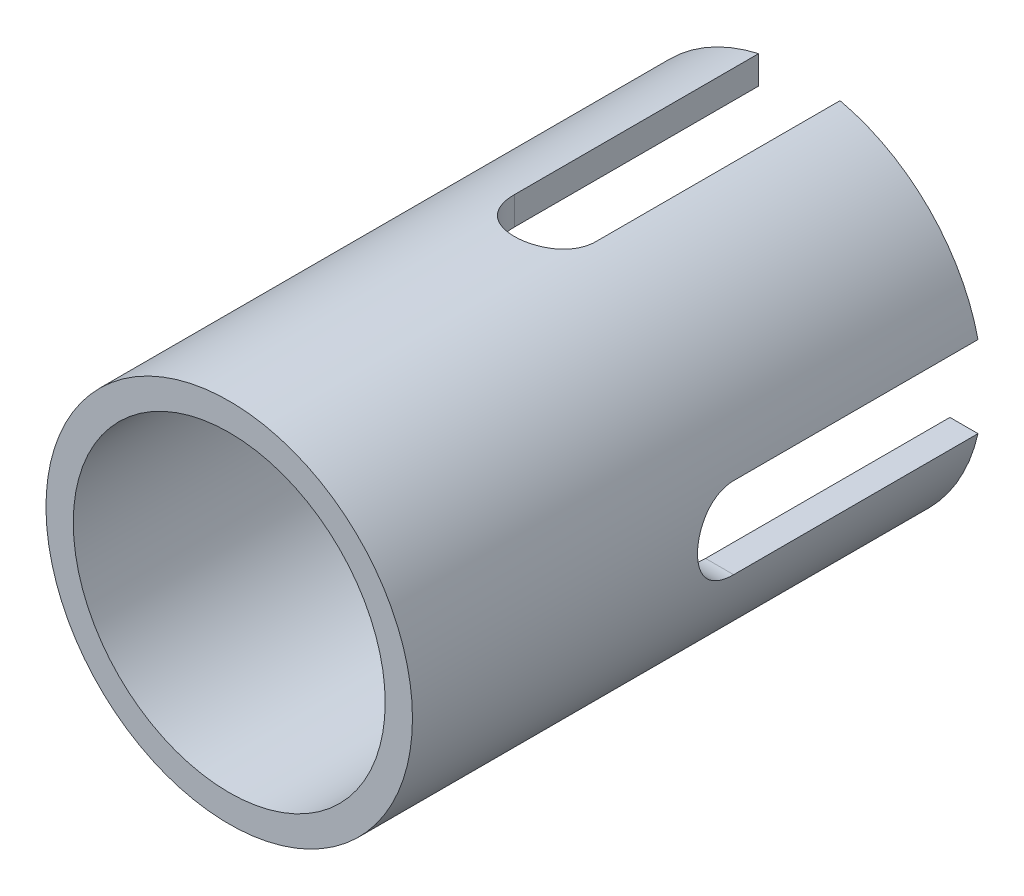
SolidWorks part; units mm, degrees
ref_plane "Front Plane" through (0, 0, 0) normal (0, 0, 1) x (1, 0, 0)
ref_plane "Top Plane" through (0, 0, 0) normal (0, 1, 0) x (1, 0, 0)
ref_plane "Right Plane" through (0, 0, 0) normal (1, 0, 0) x (0, 0, -1)
sketch "Sketch12" plane through (0, 0, 0) normal (0, 0, 1) x (1, 0, 0)
  circle A0 centre (0, 0) radius 48.641
  circle A1 centre (0, 0) radius 57.15
  dimension "D1" = 114.3
  dimension "D2" = 97.282
extrude "Boss-Extrude1" add sketch "Sketch12" along normal blind 177.8
sketch "Sketch13" plane through (0, 0, 0) normal (0, 1, 0) x (1, 0, 0)
  line L0 (-12.7, 0) -> (12.7, 0)
  line L1 (57.15, 0) -> (-57.15, 0) construction
  line L2 (12.7, 0) -> (12.7, -76.2)
  line L3 (-12.7, 0) -> (-12.7, -76.2)
  line L4 (57.15, 0) -> (12.7, 0) construction
  line L5 (-57.15, 0) -> (-12.7, 0) construction
  arc A0 (-12.7, -76.2) -> (12.7, -76.2) centre (0, -76.2) ccw
  dimension "D2" = 12.7
  dimension "D1" = 76.2
extrude "Cut-Extrude1" cut sketch "Sketch13" along normal through all both and the other way through all
pattern_circular "CirPattern1" count 2 every 90 about axis through (0, 0, 0) along (0, 0, 1) of "Cut-Extrude1"
sketch "Sketch14" plane through (0, 0, 177.8) normal (0, 0, 1) x (1, 0, 0)
  line L0 (0, 57.15) -> (0, -57.15) construction
  line L1 (57.15, 0) -> (-57.15, 0) construction
  circle A0 centre (0, 0) radius 57.15 construction
  point P8 (0, 0)
